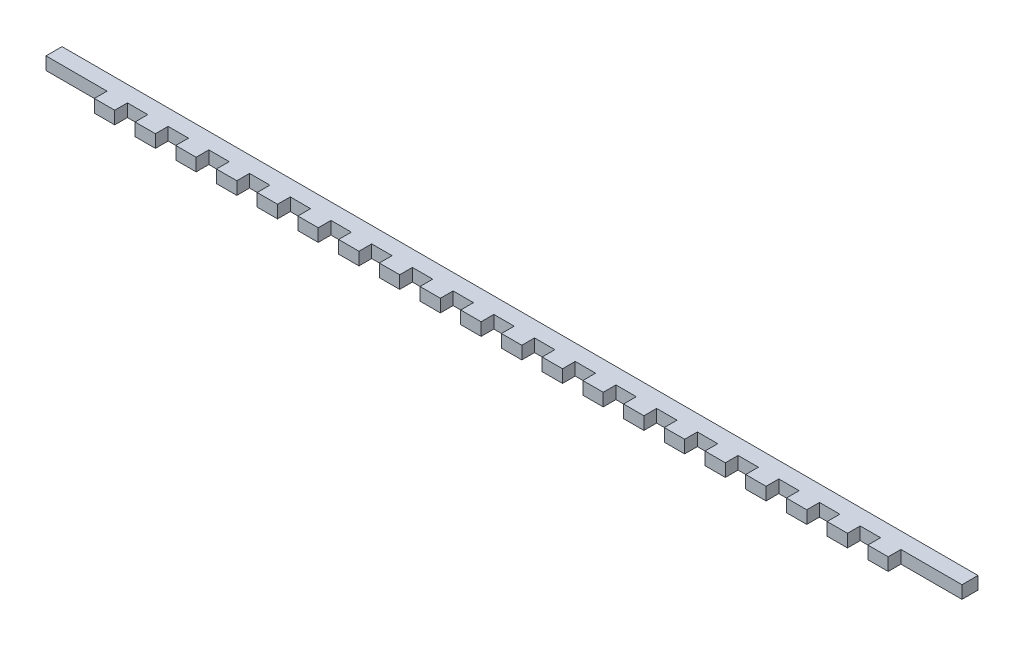
SolidWorks part; units mm, degrees
ref_plane "Front Plane" through (0, 0, 0) normal (0, 0, 1) x (1, 0, 0)
ref_plane "Top Plane" through (0, 0, 0) normal (0, 1, 0) x (1, 0, 0)
ref_plane "Right Plane" through (0, 0, 0) normal (1, 0, 0) x (0, 0, -1)
sketch "Sketch1" plane through (0, 0, 0) normal (0, 1, 0) x (1, 0, 0)
  line L0 (-171.3358, 2.0609) -> (-156.0958, 2.0609)
  line L1 (-171.3358, 6.0609) -> (57.2642, 6.0609)
  line L2 (-171.3358, 6.0609) -> (-171.3358, 2.0609)
  line L3 (-156.0958, -1.1141) -> (-151.0158, -1.1141)
  line L4 (57.2642, 6.0609) -> (57.2642, 2.0609)
  line L5 (-151.0158, 2.0609) -> (-151.0158, -1.1141)
  line L6 (-156.0958, 2.0609) -> (-156.0958, -1.1141)
  line L7 (-151.0158, 2.0609) -> (-145.9358, 2.0609)
  line L8 (-145.9358, -1.1141) -> (-140.8558, -1.1141)
  line L9 (-140.8558, 2.0609) -> (-140.8558, -1.1141)
  line L10 (-145.9358, 2.0609) -> (-145.9358, -1.1141)
  line L11 (-140.8558, 2.0609) -> (-135.7758, 2.0609)
  line L12 (-135.7758, -1.1141) -> (-130.6958, -1.1141)
  line L13 (-130.6958, 2.0609) -> (-130.6958, -1.1141)
  line L14 (-135.7758, 2.0609) -> (-135.7758, -1.1141)
  line L15 (-130.6958, 2.0609) -> (-125.6158, 2.0609)
  line L16 (-125.6158, -1.1141) -> (-120.5358, -1.1141)
  line L17 (-120.5358, 2.0609) -> (-120.5358, -1.1141)
  line L18 (-125.6158, 2.0609) -> (-125.6158, -1.1141)
  line L19 (-120.5358, 2.0609) -> (-115.4558, 2.0609)
  line L20 (-115.4558, -1.1141) -> (-110.3758, -1.1141)
  line L21 (-110.3758, 2.0609) -> (-110.3758, -1.1141)
  line L22 (-115.4558, 2.0609) -> (-115.4558, -1.1141)
  line L23 (-110.3758, 2.0609) -> (-105.2958, 2.0609)
  line L24 (-105.2958, -1.1141) -> (-100.2158, -1.1141)
  line L25 (-100.2158, 2.0609) -> (-100.2158, -1.1141)
  line L26 (-105.2958, 2.0609) -> (-105.2958, -1.1141)
  line L27 (-100.2158, 2.0609) -> (-95.1358, 2.0609)
  line L28 (-95.1358, -1.1141) -> (-90.0558, -1.1141)
  line L29 (-90.0558, 2.0609) -> (-90.0558, -1.1141)
  line L30 (-95.1358, 2.0609) -> (-95.1358, -1.1141)
  line L31 (-90.0558, 2.0609) -> (-84.9758, 2.0609)
  line L32 (-84.9758, -1.1141) -> (-79.8958, -1.1141)
  line L33 (-79.8958, 2.0609) -> (-79.8958, -1.1141)
  line L34 (-84.9758, 2.0609) -> (-84.9758, -1.1141)
  line L35 (-79.8958, 2.0609) -> (-74.8158, 2.0609)
  line L36 (-74.8158, -1.1141) -> (-69.7358, -1.1141)
  line L37 (-69.7358, 2.0609) -> (-69.7358, -1.1141)
  line L38 (-74.8158, 2.0609) -> (-74.8158, -1.1141)
  line L39 (-69.7358, 2.0609) -> (-64.6558, 2.0609)
  line L40 (-64.6558, -1.1141) -> (-59.5758, -1.1141)
  line L41 (-59.5758, 2.0609) -> (-59.5758, -1.1141)
  line L42 (-64.6558, 2.0609) -> (-64.6558, -1.1141)
  line L43 (-59.5758, 2.0609) -> (-54.4958, 2.0609)
  line L44 (-54.4958, -1.1141) -> (-49.4158, -1.1141)
  line L45 (-49.4158, 2.0609) -> (-49.4158, -1.1141)
  line L46 (-54.4958, 2.0609) -> (-54.4958, -1.1141)
  line L47 (-49.4158, 2.0609) -> (-44.3358, 2.0609)
  line L48 (-44.3358, -1.1141) -> (-39.2558, -1.1141)
  line L49 (-39.2558, 2.0609) -> (-39.2558, -1.1141)
  line L50 (-44.3358, 2.0609) -> (-44.3358, -1.1141)
  line L51 (-39.2558, 2.0609) -> (-34.1758, 2.0609)
  line L52 (-34.1758, -1.1141) -> (-29.0958, -1.1141)
  line L53 (-29.0958, 2.0609) -> (-29.0958, -1.1141)
  line L54 (-34.1758, 2.0609) -> (-34.1758, -1.1141)
  line L55 (-29.0958, 2.0609) -> (-24.0158, 2.0609)
  line L56 (-24.0158, -1.1141) -> (-18.9358, -1.1141)
  line L57 (-18.9358, 2.0609) -> (-18.9358, -1.1141)
  line L58 (-24.0158, 2.0609) -> (-24.0158, -1.1141)
  line L59 (-18.9358, 2.0609) -> (-13.8558, 2.0609)
  line L60 (-13.8558, -1.1141) -> (-8.7758, -1.1141)
  line L61 (-8.7758, 2.0609) -> (-8.7758, -1.1141)
  line L62 (-13.8558, 2.0609) -> (-13.8558, -1.1141)
  line L63 (-8.7758, 2.0609) -> (-3.6958, 2.0609)
  line L64 (-3.6958, -1.1141) -> (1.3842, -1.1141)
  line L65 (1.3842, 2.0609) -> (1.3842, -1.1141)
  line L66 (-3.6958, 2.0609) -> (-3.6958, -1.1141)
  line L67 (1.3842, 2.0609) -> (6.4642, 2.0609)
  line L68 (6.4642, -1.1141) -> (11.5442, -1.1141)
  line L69 (11.5442, 2.0609) -> (11.5442, -1.1141)
  line L70 (6.4642, 2.0609) -> (6.4642, -1.1141)
  line L71 (11.5442, 2.0609) -> (16.6242, 2.0609)
  line L72 (16.6242, -1.1141) -> (21.7042, -1.1141)
  line L73 (21.7042, 2.0609) -> (21.7042, -1.1141)
  line L74 (16.6242, 2.0609) -> (16.6242, -1.1141)
  line L75 (21.7042, 2.0609) -> (26.7842, 2.0609)
  line L76 (26.7842, -1.1141) -> (31.8642, -1.1141)
  line L77 (31.8642, 2.0609) -> (31.8642, -1.1141)
  line L78 (26.7842, 2.0609) -> (26.7842, -1.1141)
  line L79 (31.8642, 2.0609) -> (36.9442, 2.0609)
  line L80 (36.9442, -1.1141) -> (42.0242, -1.1141)
  line L81 (42.0242, 2.0609) -> (42.0242, -1.1141)
  line L82 (36.9442, 2.0609) -> (36.9442, -1.1141)
  line L84 (42.0242, 2.0609) -> (57.2642, 2.0609)
  dimension "D1" = 228.6
  dimension "D2" = 4
  dimension "D3" = 5.08
  dimension "D4" = 10.16
  dimension "D5" = 3.175
extrude "Boss-Extrude1" add sketch "Sketch1" along normal blind 3.175
sketch "Sketch2" plane through (0, 0, 0) normal (0, -1, 0) x (1, 0, 0)
